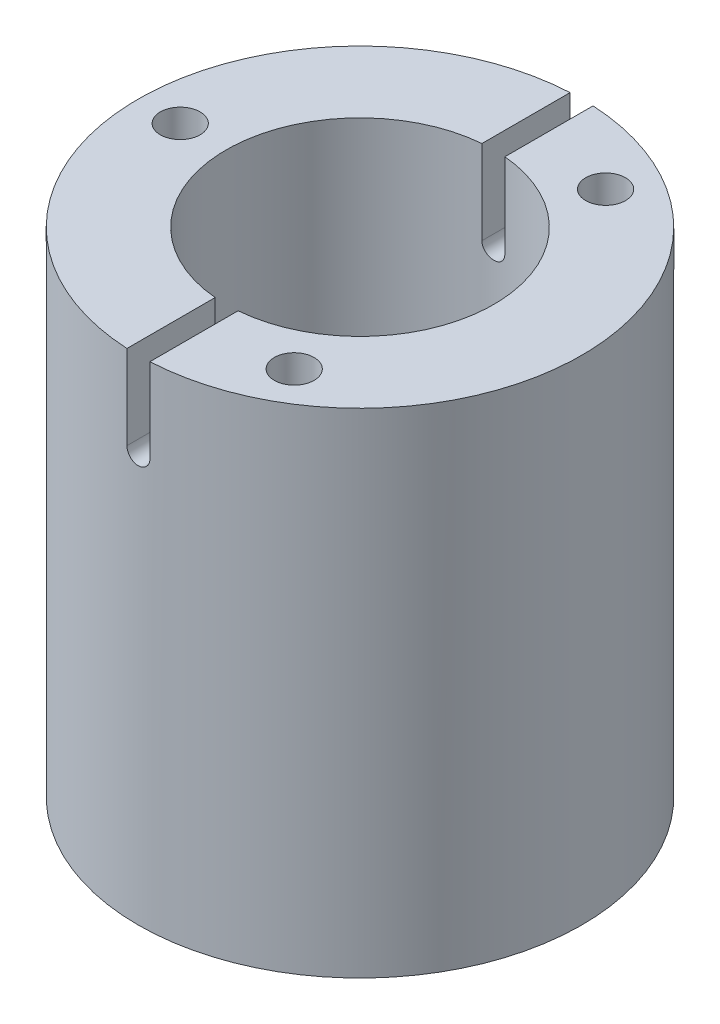
SolidWorks part; units mm, degrees
material "7075-T6 (SN)"
ref_plane "Ön Düzlem" through (0, 0, 0) normal (0, 0, 1) x (1, 0, 0)
ref_plane "Üst Düzlem" through (0, 0, 0) normal (0, 1, 0) x (1, 0, 0)
ref_plane "Sağ Düzlem" through (0, 0, 0) normal (1, 0, 0) x (0, 0, -1)
sketch "Çizim1" plane through (0, 0, 0) normal (0, 1, 0) x (1, 0, 0)
  circle A0 centre (0, 0) radius 29
  dimension "D1" = 58
extrude "Yükseklik-Ekstrüzyon1" add sketch "Çizim1" along normal blind 64.5
sketch "Çizim2" plane through (0, 64.5, 0) normal (0, 1, 0) x (1, 0, 0)
  circle A0 centre (0, 0) radius 17.5
  dimension "D1" = 35
extrude "Kes-Ekstrüzyon1" cut sketch "Çizim2" against normal blind 59.5
hole_wizard "Ø5.0 (5) Çap Delik1" positions "Çizim4" profile "Çizim5" hole size "Ø5.0" standard "DIN"
sketch "Çizim4" plane through (0, 0, 0) normal (0, -1, 0) x (-1, 0, 0)
  point P0 (0, 0)
sketch "Çizim5" plane through (0, 0, 0) normal (1, 0, 0) x (0, 0, -1)
  line L0 (0, 0) -> (0, 6.9099)
  line L1 (0, 6.9099) -> (2.5, 6)
  line L2 (2.5, 6) -> (2.5, 0)
  line L5 (2.5, 0) -> (0, 0)
  line L10 (0, 6.9099) -> (-2.5, 6) construction
  line L11 (0, -6.35) -> (0, 107.95) construction
  dimension "Hole Dia." = 5
  dimension "Hole Depth" = 6
  dimension "Drill Angle" = 140
chamfer "Pah1" distance 0.5 angle 45 1 edges at (0, 0, -2.5)
chamfer "Pah2" distance 1 angle 45 1 edges at (0, 5, 2.5)
ref_plane "Düzlem2" through (0, 0, 29) normal (0, 0, 1) x (1, 0, 0)
sketch "Çizim6" plane through (0, 0, 29) normal (0, 0, 1) x (1, 0, 0)
  line L0 (29, 64.5) -> (-29, 64.5) construction
  line L1 (0, 53.5) -> (0, 55.5) construction
  line L2 (-1.5, 53.5) -> (-1.5, 55.5)
  line L3 (1.5, 53.5) -> (1.5, 55.5)
  arc A1 (-1.5, 53.5) -> (1.5, 53.5) centre (0, 53.5) ccw
  arc A2 (1.5, 55.5) -> (-1.5, 55.5) centre (0, 55.5) ccw
  point P6 (0, 54.5)
  dimension "D1" = 10
  dimension "D3" = 3
  dimension "D4" = 5
extrude "Kes-Ekstrüzyon2" cut sketch "Çizim6" against normal through all
sketch "Çizim8" plane through (0, 0, 0) normal (0, -1, 0) x (1, 0, 0)
  line L0 (0, 0) -> (-23.5, 0) construction
  line L1 (0, 0) -> (23.5, 0) construction
  line L2 (0, 0) -> (11.75, 20.3516) construction
  line L3 (0, 0) -> (11.75, -20.3516) construction
  circle A0 centre (0, 0) radius 23.5 construction
  point P3 (0, 23.5)
  dimension "D1" = 47
  dimension "D2" = 120
  dimension "D3" = 120
sketch "Çizim15" plane through (0, 0, 29) normal (0, 0, 1) x (1, 0, 0)
  line L0 (1.5, 54.5) -> (1.5, 64.5)
  line L1 (1.5, 55.5) -> (1.5, 53.5) construction
  line L2 (17.5, 64.5) -> (-17.5, 64.5) construction
  line L3 (-1.5, 54.5) -> (-1.5, 64.5)
  line L4 (-1.5, 53.5) -> (-1.5, 55.5) construction
  line L5 (-1.5, 64.5) -> (1.5, 64.5)
  line L6 (-1.5, 54.5) -> (1.5, 54.5)
extrude "Kes-Ekstrüzyon4" cut sketch "Çizim15" against normal through all
hole_wizard "M5 Altıgen Alyan Başlı Kör Vida İçin Havşa2" positions "3B Çizim5" profile "Çizim17" counterbore size "M5" standard "DIN"
sketch3d "3B Çizim5"
  point P0 (11.75, 0, 20.3516)
  point P3 (11.75, 0, -20.3516)
  point P6 (-23.5, 0, 0)
sketch "Çizim17" plane through (11.75, 0, 20.3516) normal (1, 0, 0) x (0, 0, -1)
  line L0 (0, 0) -> (0, 88)
  line L1 (0, 88) -> (2.6, 87.0537)
  line L2 (2.6, 87.0537) -> (2.6, 6)
  line L3 (2.6, 6) -> (4.5, 6)
  line L4 (4.5, 6) -> (4.5, 0)
  line L5 (4.5, 0) -> (0, 0)
  line L10 (0, 88) -> (-2.6, 87.0537) construction
  line L11 (0, -6.35) -> (0, 107.95) construction
  dimension "Hole Dia." = 5.2
  dimension "Hole Depth" = 88
  dimension "C'Bore Dia." = 9
  dimension "C'Bore Depth" = 6
  dimension "Drill Angle" = 140
